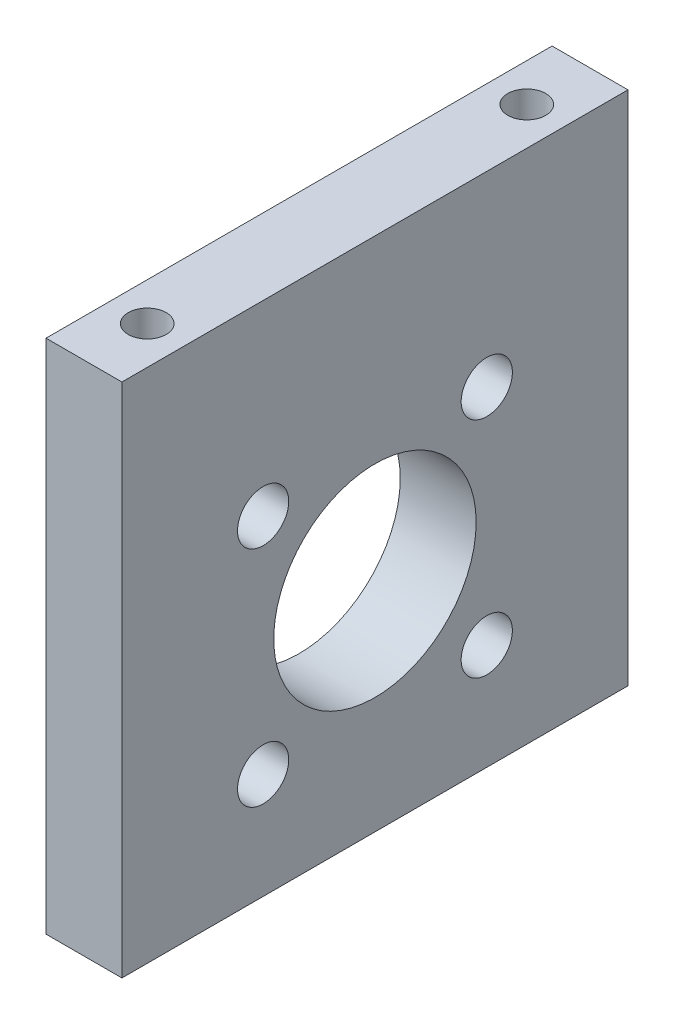
SolidWorks part; units mm, degrees
material "6061 合金"
ref_plane "前视基准面" through (0, 0, 0) normal (0, 0, 1) x (1, 0, 0)
ref_plane "上视基准面" through (0, 0, 0) normal (0, 1, 0) x (1, 0, 0)
ref_plane "右视基准面" through (0, 0, 0) normal (1, 0, 0) x (0, 0, -1)
sketch "草图1" plane through (0, 0, 0) normal (1, 0, 0) x (0, 0, -1)
  line L0 (0, 0) -> (0, 12.5) construction
  line L1 (-20, 23.6) -> (20, 23.6)
  line L2 (-20, 23.6) -> (-20, -17.2)
  line L3 (-20, -17.2) -> (20, -17.2)
  line L4 (20, 23.6) -> (20, -17.2)
  line L5 (0, 0) -> (-8.8388, 8.8388) construction
  line L6 (0, 12.5) -> (0, 23.6) construction
  circle A0 centre (0, 0) radius 8
  circle A1 centre (0, 0) radius 12.5 construction
  circle A2 centre (-8.8388, 8.8388) radius 2.025
  circle A3 centre (8.8388, 8.8388) radius 2.025
  circle A4 centre (8.8388, -8.8388) radius 2.025
  circle A5 centre (-8.8388, -8.8388) radius 2.025
  point P20 (0, 0)
  dimension "D1" = 25
  dimension "D2" = 16
  dimension "D4" = 4.05
  dimension "D3" = 45
  dimension "D6" = 40
  dimension "D7" = 17.2
  dimension "D8" = 23.6
  dimension "D5" = 4
extrude "凸台-拉伸1" add sketch "草图1" along normal blind 6
sketch "草图2" plane through (0, 0, 0) normal (0, 1, 0) x (1, 0, 0)
  line L0 (3, 20) -> (3, -20) construction
  line L1 (6, 20) -> (0, 20) construction
  line L2 (6, -20) -> (0, -20) construction
  line L3 (3, 0) -> (0, 0) construction
  circle A0 centre (3, 15) radius 1.5
  circle A1 centre (3, -15) radius 1.5
  dimension "D1" = 3
  dimension "D2" = 30
extrude "切除-拉伸1" cut sketch "草图2" against normal through all both and the other way through all
